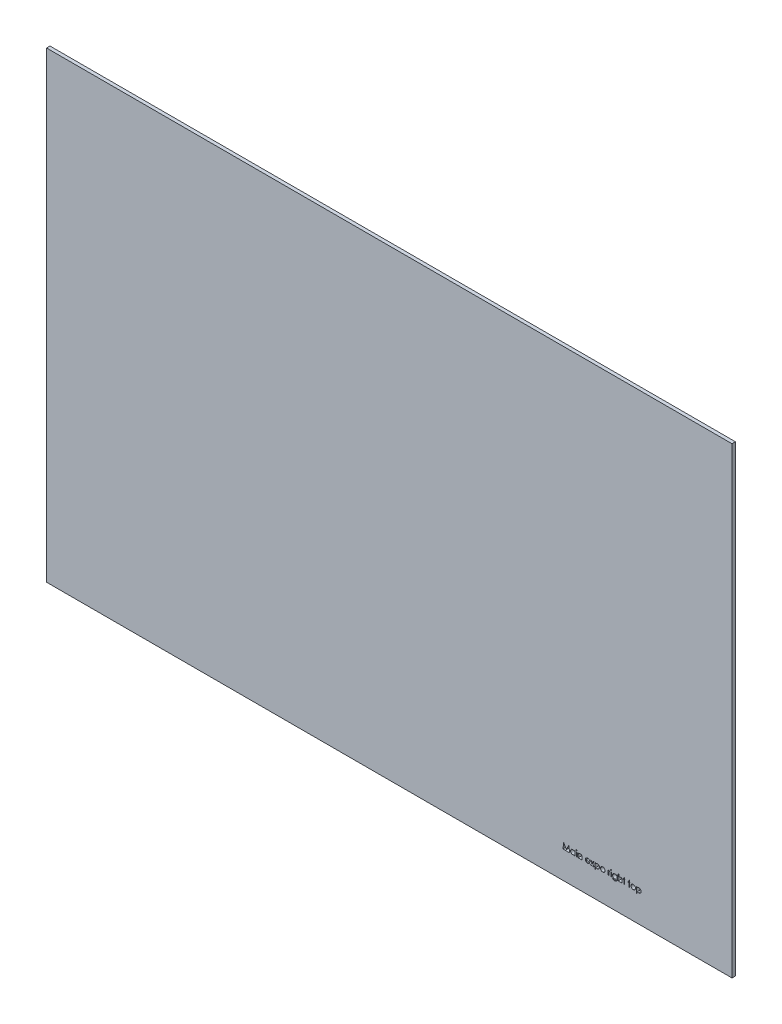
SolidWorks part; units mm, degrees
ref_plane "Front Plane" through (0, 0, 0) normal (0, 0, 1) x (1, 0, 0)
ref_plane "Top Plane" through (0, 0, 0) normal (0, 1, 0) x (1, 0, 0)
ref_plane "Right Plane" through (0, 0, 0) normal (1, 0, 0) x (0, 0, -1)
sketch "Sketch1" plane through (0, 0, 0) normal (0, 0, 1) x (1, 0, 0)
  line L0 (301.0601, -254.1343) -> (381.9081, -254.1343) construction
  line L1 (0, 0) -> (400, 0)
  line L2 (0, 0) -> (0, -270)
  line L3 (0, -270) -> (400, -270)
  line L4 (400, 0) -> (400, -270)
  line L5 (301.3293, -254.1343) -> (301.7913, -250.6343)
  line L6 (301.7913, -250.6343) -> (301.8362, -250.6343)
  line L7 (301.8362, -250.6343) -> (303.2812, -253.5061)
  line L8 (303.2812, -253.5061) -> (304.7227, -250.6343)
  line L9 (304.7227, -250.6343) -> (304.7683, -250.6343)
  line L10 (304.7683, -250.6343) -> (305.2331, -254.1343)
  line L11 (305.2331, -254.1343) -> (304.9176, -254.1343)
  line L12 (304.9176, -254.1343) -> (304.5825, -251.6158)
  line L13 (304.5825, -251.6158) -> (303.3191, -254.1343)
  line L14 (303.3191, -254.1343) -> (303.2483, -254.1343)
  line L15 (303.2483, -254.1343) -> (301.9799, -251.6102)
  line L16 (301.9799, -251.6102) -> (301.6455, -254.1343)
  line L17 (301.6455, -254.1343) -> (301.3293, -254.1343)
  line L18 (308.4639, -251.5766) -> (308.4639, -254.1343)
  line L19 (308.4639, -254.1343) -> (308.1498, -254.1343)
  line L20 (308.1498, -254.1343) -> (308.1498, -253.6919)
  line L21 (308.1498, -252.0498) -> (308.1498, -251.5766)
  line L22 (308.1498, -251.5766) -> (308.4639, -251.5766)
  line L23 (309.137, -251.5766) -> (309.4511, -251.5766)
  line L24 (309.4511, -251.5766) -> (309.4511, -254.1343)
  line L25 (309.4511, -254.1343) -> (309.137, -254.1343)
  line L26 (309.137, -254.1343) -> (309.137, -251.5766)
  line L27 (310.2139, -251.5766) -> (310.528, -251.5766)
  line L28 (310.528, -251.5766) -> (310.528, -252.0379)
  line L29 (312.4575, -252.8281) -> (312.4575, -254.1343)
  line L30 (312.4575, -254.1343) -> (312.1434, -254.1343)
  line L31 (312.1434, -254.1343) -> (312.1434, -252.9312)
  line L32 (310.528, -253.2095) -> (310.528, -254.1343)
  line L33 (310.528, -254.1343) -> (310.2139, -254.1343)
  line L34 (310.2139, -254.1343) -> (310.2139, -251.5766)
  line L35 (316.6208, -253.3266) -> (316.8998, -253.4731)
  line L36 (317.0344, -252.9227) -> (314.746, -252.9227)
  line L37 (314.7789, -252.6086) -> (316.7203, -252.6086)
  line L38 (317.4383, -251.5766) -> (317.812, -251.5766)
  line L39 (317.812, -251.5766) -> (318.4703, -252.4993)
  line L40 (318.4703, -252.4993) -> (319.1287, -251.5766)
  line L41 (319.1287, -251.5766) -> (319.5024, -251.5766)
  line L42 (319.5024, -251.5766) -> (318.6575, -252.7608)
  line L43 (318.6575, -252.7608) -> (319.637, -254.1343)
  line L44 (319.637, -254.1343) -> (319.2633, -254.1343)
  line L45 (319.2633, -254.1343) -> (318.4703, -253.023)
  line L46 (318.4703, -253.023) -> (317.6774, -254.1343)
  line L47 (317.6774, -254.1343) -> (317.3037, -254.1343)
  line L48 (317.3037, -254.1343) -> (318.2838, -252.7608)
  line L49 (318.2838, -252.7608) -> (317.4383, -251.5766)
  line L50 (319.996, -251.5766) -> (320.3101, -251.5766)
  line L51 (320.3101, -251.5766) -> (320.3101, -252.0498)
  line L52 (320.3101, -253.6708) -> (320.3101, -255.0766)
  line L53 (320.3101, -255.0766) -> (319.996, -255.0766)
  line L54 (319.996, -255.0766) -> (319.996, -251.5766)
  line L55 (327.7588, -251.5766) -> (328.0729, -251.5766)
  line L56 (328.0729, -251.5766) -> (328.0729, -251.9531)
  line L57 (328.9703, -251.6194) -> (328.7979, -251.8914)
  line L58 (328.0729, -253.2747) -> (328.0729, -254.1343)
  line L59 (328.0729, -254.1343) -> (327.7588, -254.1343)
  line L60 (327.7588, -254.1343) -> (327.7588, -251.5766)
  line L61 (329.2396, -251.5766) -> (329.5537, -251.5766)
  line L62 (329.5537, -251.5766) -> (329.5537, -254.1343)
  line L63 (329.5537, -254.1343) -> (329.2396, -254.1343)
  line L64 (329.2396, -254.1343) -> (329.2396, -251.5766)
  line L65 (332.5601, -251.5766) -> (332.8742, -251.5766)
  line L66 (332.8742, -251.5766) -> (332.8742, -253.6063)
  line L67 (330.2716, -254.3138) -> (330.5857, -254.3138)
  line L68 (332.5601, -253.7767) -> (332.5601, -253.6442)
  line L69 (332.5601, -252.0239) -> (332.5601, -251.5766)
  line L70 (333.5921, -250.5445) -> (333.9062, -250.5445)
  line L71 (333.9062, -250.5445) -> (333.9062, -252.0597)
  line L72 (335.8357, -252.8281) -> (335.8357, -254.1343)
  line L73 (335.8357, -254.1343) -> (335.5216, -254.1343)
  line L74 (335.5216, -254.1343) -> (335.5216, -252.9312)
  line L75 (333.9062, -253.2095) -> (333.9062, -254.1343)
  line L76 (333.9062, -254.1343) -> (333.5921, -254.1343)
  line L77 (333.5921, -254.1343) -> (333.5921, -250.5445)
  line L78 (336.8678, -250.5445) -> (337.1819, -250.5445)
  line L79 (337.1819, -250.5445) -> (337.1819, -251.5766)
  line L80 (337.1819, -251.5766) -> (337.6306, -251.5766)
  line L81 (337.6306, -251.5766) -> (337.6306, -251.8907)
  line L82 (337.6306, -251.8907) -> (337.1819, -251.8907)
  line L83 (337.1819, -251.8907) -> (337.1819, -254.1343)
  line L84 (337.1819, -254.1343) -> (336.8678, -254.1343)
  line L85 (336.8678, -254.1343) -> (336.8678, -251.8907)
  line L86 (336.8678, -251.8907) -> (336.419, -251.8907)
  line L87 (336.419, -251.8907) -> (336.419, -251.5766)
  line L88 (336.419, -251.5766) -> (336.8678, -251.5766)
  line L89 (336.8678, -251.5766) -> (336.8678, -250.5445)
  line L90 (339.8293, -250.5445) -> (340.1434, -250.5445)
  line L91 (340.1434, -250.5445) -> (340.1434, -251.5766)
  line L92 (340.1434, -251.5766) -> (340.5921, -251.5766)
  line L93 (340.5921, -251.5766) -> (340.5921, -251.8907)
  line L94 (340.5921, -251.8907) -> (340.1434, -251.8907)
  line L95 (340.1434, -251.8907) -> (340.1434, -254.1343)
  line L96 (340.1434, -254.1343) -> (339.8293, -254.1343)
  line L97 (339.8293, -254.1343) -> (339.8293, -251.8907)
  line L98 (339.8293, -251.8907) -> (339.3806, -251.8907)
  line L99 (339.3806, -251.8907) -> (339.3806, -251.5766)
  line L100 (339.3806, -251.5766) -> (339.8293, -251.5766)
  line L101 (339.8293, -251.5766) -> (339.8293, -250.5445)
  line L102 (344.3165, -251.5766) -> (344.6306, -251.5766)
  line L103 (344.6306, -251.5766) -> (344.6306, -252.0498)
  line L104 (344.6306, -253.6708) -> (344.6306, -255.0766)
  line L105 (344.6306, -255.0766) -> (344.3165, -255.0766)
  line L106 (344.3165, -255.0766) -> (344.3165, -251.5766)
  spline S0 degree 3 poles (308.1498, -253.6919) (308.0826, -253.7713) (307.9741, -253.8818) (307.8074, -253.9965) (307.6788, -254.0647) (307.5438, -254.1158) (307.3538, -254.1652) (307.2054, -254.18) (307.1051, -254.1791) knots 0 0 0 0 0.262085 0.38627 0.507165 0.6273 0.748145 1 1 1 1
  spline S1 degree 3 poles (307.1051, -254.1791) (307.0161, -254.1789) (306.8838, -254.1674) (306.7138, -254.1266) (306.5925, -254.0847) (306.4768, -254.0291) (306.3658, -253.9626) (306.2599, -253.8833) (306.1608, -253.7928) (306.0696, -253.6944) (305.9895, -253.5894) (305.9228, -253.4784) (305.867, -253.3626) (305.824, -253.2413) (305.7833, -253.0706) (305.7718, -252.9379) (305.7716, -252.8484) knots 0 0 0 0 0.127433 0.189004 0.24993 0.310668 0.372329 0.434939 0.499576 0.564191 0.626735 0.688109 0.749294 0.810331 0.871901 1 1 1 1
  spline S2 degree 3 poles (305.7716, -252.8484) (305.7721, -252.7606) (305.7829, -252.63) (305.8249, -252.4623) (305.8684, -252.3429) (305.9242, -252.2286) (305.9921, -252.1192) (306.0722, -252.0144) (306.1644, -251.9167) (306.2643, -251.8265) (306.3713, -251.7481) (306.4825, -251.6804) (306.5997, -251.6267) (306.7213, -251.5833) (306.8925, -251.5427) (307.0255, -251.5325) (307.115, -251.5317) knots 0 0 0 0 0.126079 0.186904 0.247574 0.308003 0.369132 0.432033 0.496791 0.561611 0.624914 0.686726 0.748079 0.809582 0.871631 1 1 1 1
  spline S3 degree 3 poles (307.115, -251.5317) (307.2172, -251.532) (307.3689, -251.5451) (307.5609, -251.5991) (307.6956, -251.653) (307.8227, -251.7247) (307.9846, -251.8478) (308.0879, -251.9649) (308.1498, -252.0498) knots 0 0 0 0 0.254654 0.376015 0.495255 0.614798 0.738106 1 1 1 1
  spline S4 degree 3 poles (307.1192, -251.8458) (307.0287, -251.8462) (306.8933, -251.8612) (306.7223, -251.9178) (306.6013, -251.975) (306.4887, -252.047) (306.388, -252.1342) (306.2984, -252.234) (306.2231, -252.3461) (306.1618, -252.4663) (306.1039, -252.6334) (306.0846, -252.7644) (306.0857, -252.8519) knots 0 0 0 0 0.169593 0.252476 0.336244 0.419505 0.502036 0.584775 0.669846 0.754185 0.836658 1 1 1 1
  spline S5 degree 3 poles (306.0857, -252.8519) (306.0865, -252.9388) (306.1031, -253.0704) (306.163, -253.2372) (306.2242, -253.3584) (306.3009, -253.471) (306.3897, -253.5727) (306.4917, -253.6602) (306.6046, -253.7335) (306.7252, -253.7926) (306.8947, -253.8479) (307.0275, -253.8655) (307.1164, -253.865) knots 0 0 0 0 0.162859 0.245484 0.330807 0.416493 0.499893 0.583048 0.667158 0.751312 0.833785 1 1 1 1
  spline S6 degree 3 poles (307.1164, -253.865) (307.2067, -253.8647) (307.3423, -253.849) (307.5151, -253.793) (307.6389, -253.7351) (307.7542, -253.6634) (307.8577, -253.5794) (307.9452, -253.4817) (308.0195, -253.3743) (308.0776, -253.2566) (308.1351, -253.0872) (308.1493, -252.9517) (308.1498, -252.861) knots 0 0 0 0 0.168664 0.252552 0.33824 0.423103 0.505556 0.586176 0.667136 0.748499 0.830452 1 1 1 1
  spline S7 degree 3 poles (308.1498, -252.861) (308.1496, -252.7915) (308.1408, -252.6885) (308.1096, -252.5563) (308.0772, -252.4628) (308.0347, -252.3742) (307.9835, -252.2897) (307.9226, -252.2099) (307.853, -252.1357) (307.7768, -252.0681) (307.6962, -252.0078) (307.6103, -251.9582) (307.5204, -251.9171) (307.4263, -251.8845) (307.2927, -251.8548) (307.1893, -251.8448) (307.1192, -251.8458) knots 0 0 0 0 0.129188 0.191219 0.251913 0.312507 0.373494 0.435152 0.498741 0.562095 0.624187 0.685476 0.746097 0.807612 0.869967 1 1 1 1
  spline S8 degree 3 poles (309.2926, -250.4997) (309.3306, -250.4997) (309.388, -250.5084) (309.4558, -250.5432) (309.5003, -250.5777) (309.5385, -250.6182) (309.5745, -250.6813) (309.5859, -250.7346) (309.5857, -250.7703) knots 0 0 0 0 0.258284 0.384341 0.51198 0.638632 0.75923 1 1 1 1
  spline S9 degree 3 poles (309.5857, -250.7703) (309.5858, -250.8052) (309.5745, -250.8577) (309.5383, -250.9196) (309.5004, -250.9601) (309.4557, -250.9946) (309.388, -251.0294) (309.3306, -251.038) (309.2926, -251.0381) knots 0 0 0 0 0.237546 0.357497 0.484917 0.613329 0.74015 1 1 1 1
  spline S10 degree 3 poles (309.2926, -251.0381) (309.2552, -251.0384) (309.1987, -251.0289) (309.1317, -250.9945) (309.087, -250.9604) (309.0498, -250.9194) (309.0135, -250.8578) (309.0023, -250.8052) (309.0024, -250.7703) knots 0 0 0 0 0.256661 0.384213 0.513365 0.640443 0.761085 1 1 1 1
  spline S11 degree 3 poles (309.0024, -250.7703) (309.0022, -250.7347) (309.0135, -250.6813) (309.0496, -250.6185) (309.087, -250.5774) (309.1317, -250.5432) (309.1987, -250.5088) (309.2552, -250.4994) (309.2926, -250.4997) knots 0 0 0 0 0.242149 0.363437 0.489745 0.618115 0.744894 1 1 1 1
  spline S12 degree 3 poles (310.528, -252.0379) (310.5914, -251.9557) (310.6923, -251.8408) (310.8496, -251.7202) (310.9696, -251.6501) (311.0952, -251.5973) (311.2707, -251.5457) (311.4087, -251.5322) (311.5012, -251.5317) knots 0 0 0 0 0.273569 0.398988 0.51993 0.63811 0.756589 1 1 1 1
  spline S13 degree 3 poles (311.5012, -251.5317) (311.5936, -251.5323) (311.7314, -251.5473) (311.902, -251.6101) (312.0186, -251.6732) (312.1237, -251.7519) (312.2161, -251.8434) (312.2924, -251.9488) (312.3436, -252.0465) (312.3774, -252.1332) (312.3986, -252.2074) (312.4166, -252.2901) (312.4323, -252.3811) (312.4428, -252.4809) (312.4544, -252.6306) (312.4583, -252.7474) (312.4575, -252.8281) knots 0 0 0 0 0.151178 0.223488 0.295543 0.366976 0.437131 0.507044 0.57856 0.616614 0.658756 0.704491 0.754803 0.809332 0.868274 1 1 1 1
  spline S14 degree 3 poles (312.1434, -252.9312) (312.1429, -252.8645) (312.1428, -252.7692) (312.1389, -252.6479) (312.1349, -252.5705) (312.1291, -252.5022) (312.1218, -252.4292) (312.1133, -252.3793) (312.1062, -252.3492) knots 0 0 0 0 0.34211 0.489826 0.623254 0.74008 0.841483 1 1 1 1
  spline S15 degree 3 poles (312.1062, -252.3492) (312.0887, -252.2724) (312.049, -252.1628) (311.9608, -252.0412) (311.8829, -251.969) (311.7917, -251.9129) (311.6473, -251.8587) (311.5281, -251.8453) (311.4465, -251.8458) knots 0 0 0 0 0.260833 0.378476 0.493178 0.609281 0.729981 1 1 1 1
  spline S16 degree 3 poles (311.4465, -251.8458) (311.3965, -251.8456) (311.3218, -251.8513) (311.2251, -251.8722) (311.1547, -251.893) (311.0872, -251.9217) (311.0205, -251.9542) (310.9569, -251.9948) (310.8953, -252.0399) (310.838, -252.09) (310.7847, -252.1429) (310.7372, -252.1991) (310.6941, -252.2579) (310.6569, -252.3201) (310.6134, -252.4068) (310.589, -252.4758) (310.5764, -252.5231) knots 0 0 0 0 0.126627 0.188984 0.25023 0.312351 0.374574 0.438148 0.50292 0.567974 0.630771 0.692935 0.754398 0.815218 0.876117 1 1 1 1
  spline S17 degree 3 poles (310.5764, -252.5231) (310.567, -252.5605) (310.5566, -252.622) (310.5462, -252.7109) (310.5392, -252.7918) (310.5349, -252.8825) (310.5283, -253.0227) (310.5285, -253.1329) (310.528, -253.2095) knots 0 0 0 0 0.167615 0.271052 0.38946 0.520843 0.666399 1 1 1 1
  spline S18 degree 3 poles (316.8998, -253.4731) (316.8583, -253.5508) (316.7888, -253.6598) (316.6819, -253.7896) (316.5968, -253.8713) (316.5071, -253.9426) (316.4124, -254.0049) (316.3121, -254.058) (316.2063, -254.1028) (316.094, -254.1372) (315.9316, -254.1705) (315.8047, -254.1791) (315.7184, -254.1791) knots 0 0 0 0 0.181661 0.265874 0.346355 0.4246 0.501903 0.579992 0.658443 0.738672 0.821894 1 1 1 1
  spline S19 degree 3 poles (315.7184, -254.1791) (315.6227, -254.1791) (315.4817, -254.1681) (315.3025, -254.125) (315.1793, -254.081) (315.0645, -254.0236) (314.958, -253.9536) (314.8592, -253.8715) (314.7712, -253.7765) (314.692, -253.6748) (314.622, -253.5689) (314.5636, -253.4589) (314.516, -253.3456) (314.4776, -253.2298) (314.4416, -253.0693) (314.4328, -252.9455) (314.4319, -252.8624) knots 0 0 0 0 0.139629 0.204797 0.268135 0.329814 0.391301 0.453434 0.516552 0.579631 0.641119 0.701294 0.76081 0.819932 0.87892 1 1 1 1
  spline S20 degree 3 poles (314.4319, -252.8624) (314.4328, -252.7846) (314.4401, -252.6685) (314.4717, -252.518) (314.5039, -252.4091) (314.5454, -252.3035) (314.6136, -252.166) (314.6788, -252.07) (314.7263, -252.0085) knots 0 0 0 0 0.253768 0.377428 0.500551 0.623296 0.746578 1 1 1 1
  spline S21 degree 3 poles (314.7263, -252.0085) (314.7869, -251.9327) (314.8857, -251.8269) (315.0403, -251.7161) (315.1619, -251.6481) (315.2923, -251.5964) (315.4788, -251.5439) (315.6267, -251.5329) (315.7261, -251.5317) knots 0 0 0 0 0.253589 0.374643 0.49534 0.616325 0.739759 1 1 1 1
  spline S22 degree 3 poles (315.7261, -251.5317) (315.829, -251.5313) (315.9809, -251.5462) (316.1735, -251.5994) (316.3073, -251.6545) (316.433, -251.7257) (316.5913, -251.8448) (316.6947, -251.9545) (316.7561, -252.0351) knots 0 0 0 0 0.259033 0.38188 0.502258 0.622752 0.744743 1 1 1 1
  spline S23 degree 3 poles (316.7561, -252.0351) (316.802, -252.094) (316.8619, -252.1896) (316.9255, -252.3264) (316.9639, -252.4353) (316.9949, -252.5491) (317.0255, -252.7115) (317.0328, -252.8375) (317.0344, -252.9227) knots 0 0 0 0 0.236255 0.356174 0.47725 0.60154 0.729618 1 1 1 1
  spline S24 degree 3 poles (314.746, -252.9227) (314.7478, -252.989) (314.7566, -253.0868) (314.7869, -253.2121) (314.8182, -253.2991) (314.856, -253.3821) (314.9024, -253.4602) (314.9578, -253.5333) (315.0195, -253.6018) (315.0882, -253.6629) (315.1605, -253.7175) (315.2374, -253.7633) (315.3183, -253.8005) (315.403, -253.8296) (315.523, -253.8567) (315.6162, -253.8654) (315.6792, -253.865) knots 0 0 0 0 0.134476 0.198391 0.260753 0.321829 0.383037 0.444653 0.507398 0.569825 0.630778 0.690929 0.750945 0.811049 0.872331 1 1 1 1
  spline S25 degree 3 poles (315.6792, -253.865) (315.7414, -253.8653) (315.8347, -253.858) (315.9565, -253.8325) (316.0458, -253.8066) (316.1313, -253.7751) (316.2106, -253.737) (316.2835, -253.6948) (316.3516, -253.6466) (316.4176, -253.5876) (316.5111, -253.4828) (316.5782, -253.3931) (316.6208, -253.3266) knots 0 0 0 0 0.163879 0.245659 0.327726 0.40861 0.485749 0.559169 0.630268 0.705306 0.792065 1 1 1 1
  spline S26 degree 3 poles (316.7203, -252.6086) (316.7005, -252.5279) (316.6608, -252.414) (316.5884, -252.2771) (316.5268, -252.1915) (316.457, -252.1155) (316.3763, -252.0491) (316.2859, -251.9896) (316.1861, -251.9395) (316.0805, -251.8968) (315.9327, -251.8583) (315.8187, -251.8447) (315.7423, -251.8458) knots 0 0 0 0 0.185231 0.267501 0.3444 0.419595 0.496891 0.576638 0.660268 0.745387 0.83004 1 1 1 1
  spline S27 degree 3 poles (315.7423, -251.8458) (315.6803, -251.8457) (315.5883, -251.8524) (315.47, -251.8781) (315.3853, -251.904) (315.3046, -251.9386) (315.1996, -251.9931) (315.1287, -252.0473) (315.0832, -252.0856) knots 0 0 0 0 0.259141 0.384162 0.505992 0.629098 0.750669 1 1 1 1
  spline S28 degree 3 poles (315.0832, -252.0856) (315.0483, -252.115) (315.0011, -252.1659) (314.9444, -252.2406) (314.905, -252.3037) (314.869, -252.3723) (314.8228, -252.4729) (314.7954, -252.5533) (314.7789, -252.6086) knots 0 0 0 0 0.22258 0.3385 0.458709 0.585535 0.717518 1 1 1 1
  spline S29 degree 3 poles (320.3101, -252.0498) (320.3722, -251.9645) (320.4767, -251.8486) (320.6379, -251.7244) (320.7651, -251.653) (320.8995, -251.5992) (321.0907, -251.5451) (321.2418, -251.532) (321.3435, -251.5317) knots 0 0 0 0 0.263045 0.386061 0.505771 0.625178 0.746148 1 1 1 1
  spline S30 degree 3 poles (321.3435, -251.5317) (321.4332, -251.5326) (321.5664, -251.5426) (321.7379, -251.5833) (321.8594, -251.6267) (321.9767, -251.6804) (322.0879, -251.7481) (322.1948, -251.8265) (322.2948, -251.9167) (322.3871, -252.0144) (322.4669, -252.1194) (322.5358, -252.2283) (322.5915, -252.3429) (322.635, -252.4622) (322.677, -252.63) (322.6878, -252.7606) (322.6883, -252.8484) knots 0 0 0 0 0.128636 0.190653 0.252125 0.313446 0.375227 0.438498 0.503285 0.56801 0.630879 0.692154 0.752552 0.813191 0.873985 1 1 1 1
  spline S31 degree 3 poles (322.6883, -252.8484) (322.6881, -252.9379) (322.6766, -253.0706) (322.6359, -253.2413) (322.5929, -253.3626) (322.5372, -253.4786) (322.4695, -253.5892) (322.3896, -253.6944) (322.2983, -253.7927) (322.1993, -253.8833) (322.0934, -253.9626) (321.9824, -254.0291) (321.8667, -254.0847) (321.7454, -254.1266) (321.5751, -254.1675) (321.4426, -254.1788) (321.3533, -254.1791) knots 0 0 0 0 0.128034 0.189574 0.25058 0.311733 0.37325 0.435763 0.500346 0.564949 0.627528 0.689157 0.749865 0.81076 0.8723 1 1 1 1
  spline S32 degree 3 poles (321.3533, -254.1791) (321.2529, -254.1803) (321.1044, -254.1631) (320.914, -254.1106) (320.7798, -254.054) (320.6517, -253.9817) (320.4866, -253.8622) (320.3776, -253.751) (320.3101, -253.6708) knots 0 0 0 0 0.250548 0.37123 0.492116 0.613401 0.737997 1 1 1 1
  spline S33 degree 3 poles (321.3407, -251.8458) (321.2706, -251.8448) (321.1672, -251.8549) (321.0335, -251.8845) (320.9394, -251.9173) (320.8492, -251.9577) (320.7635, -252.0082) (320.6824, -252.0679) (320.6062, -252.1356) (320.5373, -252.2101) (320.4764, -252.2897) (320.4252, -252.3742) (320.3826, -252.4628) (320.3503, -252.5563) (320.3191, -252.6885) (320.3103, -252.7915) (320.3101, -252.861) knots 0 0 0 0 0.130024 0.192374 0.253884 0.314896 0.375806 0.438242 0.501591 0.564881 0.626533 0.687516 0.748106 0.808796 0.870822 1 1 1 1
  spline S34 degree 3 poles (320.3101, -252.861) (320.3102, -252.9518) (320.3254, -253.0869) (320.3814, -253.2567) (320.4399, -253.3742) (320.5138, -253.4822) (320.6029, -253.5789) (320.7064, -253.6637) (320.8224, -253.7351) (320.9469, -253.793) (321.12, -253.8487) (321.2555, -253.8649) (321.3456, -253.865) knots 0 0 0 0 0.169344 0.251061 0.332326 0.413189 0.494299 0.576654 0.661785 0.747765 0.831967 1 1 1 1
  spline S35 degree 3 poles (321.3456, -253.865) (321.4341, -253.8656) (321.5663, -253.8477) (321.7352, -253.7928) (321.8554, -253.7333) (321.9682, -253.6603) (322.0701, -253.5727) (322.1591, -253.4712) (322.235, -253.3582) (322.296, -253.237) (322.3573, -253.0706) (322.3732, -252.9387) (322.3742, -252.8519) knots 0 0 0 0 0.165574 0.248159 0.332033 0.416257 0.499525 0.583039 0.668596 0.754035 0.83692 1 1 1 1
  spline S36 degree 3 poles (322.3742, -252.8519) (322.3754, -252.7644) (322.3558, -252.6335) (322.2983, -252.4661) (322.2358, -252.3465) (322.1616, -252.2338) (322.0719, -252.1342) (321.9712, -252.047) (321.8586, -251.975) (321.7376, -251.9178) (321.5666, -251.8612) (321.4312, -251.8462) (321.3407, -251.8458) knots 0 0 0 0 0.163349 0.245826 0.330367 0.415198 0.497941 0.580476 0.66374 0.747513 0.830399 1 1 1 1
  spline S37 degree 3 poles (324.5519, -251.5317) (324.6459, -251.5307) (324.7852, -251.5443) (324.9633, -251.5889) (325.0891, -251.6342) (325.2075, -251.6949) (325.3598, -251.7924) (325.4615, -251.8851) (325.5236, -251.9531) knots 0 0 0 0 0.258332 0.382134 0.503804 0.624693 0.746871 1 1 1 1
  spline S38 degree 3 poles (325.5236, -251.9531) (325.5806, -252.0154) (325.657, -252.1154) (325.7393, -252.2597) (325.7884, -252.3719) (325.827, -252.4883) (325.8642, -252.6513) (325.8737, -252.7775) (325.8742, -252.8624) knots 0 0 0 0 0.253834 0.376506 0.498534 0.621368 0.744565 1 1 1 1
  spline S39 degree 3 poles (325.8742, -252.8624) (325.8747, -252.948) (325.863, -253.0751) (325.8243, -253.2395) (325.7836, -253.3574) (325.7312, -253.4713) (325.6673, -253.5807) (325.5914, -253.6858) (325.5054, -253.7858) (325.4104, -253.878) (325.3073, -253.9583) (325.1981, -254.0271) (325.0815, -254.0826) (324.9584, -254.1263) (324.7823, -254.1681) (324.6448, -254.1788) (324.5519, -254.1791) knots 0 0 0 0 0.123337 0.183265 0.243172 0.302898 0.363774 0.425605 0.489659 0.553785 0.616222 0.677854 0.739517 0.802097 0.865866 1 1 1 1
  spline S40 degree 3 poles (324.5519, -254.1791) (324.4585, -254.1787) (324.3204, -254.1682) (324.1439, -254.1263) (324.0207, -254.0824) (323.9035, -254.0271) (323.7938, -253.9585) (323.6906, -253.878) (323.5955, -253.7858) (323.5095, -253.6858) (323.4336, -253.5807) (323.3697, -253.4713) (323.3174, -253.3574) (323.2766, -253.2395) (323.2379, -253.0751) (323.2262, -252.948) (323.2267, -252.8624) knots 0 0 0 0 0.134635 0.198324 0.260825 0.322714 0.384555 0.446913 0.510958 0.574931 0.636685 0.697483 0.757134 0.816966 0.876818 1 1 1 1
  spline S41 degree 3 poles (323.2267, -252.8624) (323.2272, -252.7777) (323.2368, -252.6517) (323.2738, -252.4892) (323.3125, -252.3733) (323.362, -252.2616) (323.4432, -252.1168) (323.5209, -252.0177) (323.5773, -251.9552) knots 0 0 0 0 0.255238 0.378679 0.501088 0.622714 0.746241 1 1 1 1
  spline S42 degree 3 poles (323.5773, -251.9552) (323.6389, -251.8863) (323.7414, -251.7945) (323.8934, -251.695) (324.0131, -251.6355) (324.1388, -251.5887) (324.3177, -251.5443) (324.4573, -251.5308) (324.5519, -251.5317) knots 0 0 0 0 0.252713 0.374819 0.496436 0.617911 0.741288 1 1 1 1
  spline S43 degree 3 poles (324.5505, -251.8458) (324.4835, -251.846) (324.3839, -251.855) (324.256, -251.8861) (324.1645, -251.9187) (324.0769, -251.9608) (323.993, -252.0125) (323.9125, -252.0732) (323.8372, -252.1426) (323.768, -252.2185) (323.7075, -252.2993) (323.6561, -252.3839) (323.6132, -252.4721) (323.5814, -252.565) (323.5499, -252.6952) (323.541, -252.7964) (323.5408, -252.8645) knots 0 0 0 0 0.126044 0.187165 0.247399 0.30838 0.36978 0.432584 0.497641 0.562401 0.625557 0.687332 0.748313 0.809791 0.871768 1 1 1 1
  spline S44 degree 3 poles (323.5408, -252.8645) (323.5411, -252.9532) (323.5567, -253.0865) (323.615, -253.2545) (323.6735, -253.3741) (323.747, -253.4848) (323.8334, -253.5835) (323.9321, -253.6687) (324.0417, -253.7394) (324.16, -253.7954) (324.3284, -253.8493) (324.4612, -253.8661) (324.5505, -253.865) knots 0 0 0 0 0.168179 0.251488 0.335841 0.419834 0.502345 0.583649 0.665931 0.748717 0.831047 1 1 1 1
  spline S45 degree 3 poles (324.5505, -253.865) (324.6397, -253.8659) (324.7723, -253.8496) (324.9403, -253.7953) (325.0586, -253.7394) (325.1681, -253.6684) (325.2675, -253.584) (325.3532, -253.4845) (325.4266, -253.374) (325.4861, -253.2547) (325.5441, -253.0865) (325.5599, -252.9533) (325.5601, -252.8645) knots 0 0 0 0 0.168983 0.250908 0.333708 0.416005 0.49766 0.579893 0.663902 0.748466 0.831791 1 1 1 1
  spline S46 degree 3 poles (325.5601, -252.8645) (325.5599, -252.7964) (325.551, -252.6952) (325.5196, -252.565) (325.4876, -252.4721) (325.445, -252.3836) (325.3926, -252.2996) (325.3323, -252.2182) (325.2623, -252.1429) (325.187, -252.0731) (325.1065, -252.0125) (325.0228, -251.961) (324.9354, -251.9184) (324.8439, -251.8864) (324.7164, -251.8548) (324.6172, -251.8462) (324.5505, -251.8458) knots 0 0 0 0 0.128274 0.19027 0.251768 0.312769 0.374793 0.43797 0.503047 0.568125 0.63095 0.692369 0.752973 0.813641 0.874355 1 1 1 1
  spline S47 degree 3 poles (328.0729, -251.9531) (328.1159, -251.8854) (328.1839, -251.7916) (328.2897, -251.6889) (328.3673, -251.6304) (328.4477, -251.5866) (328.5553, -251.5439) (328.6408, -251.5321) (328.6969, -251.5317) knots 0 0 0 0 0.306112 0.438367 0.560541 0.675317 0.786114 1 1 1 1
  spline S48 degree 3 poles (328.6969, -251.5317) (328.7419, -251.5321) (328.8383, -251.549) (328.926, -251.5925) (328.9703, -251.6194) knots 0 0 0 0 0.463523 1 1 1 1
  spline S49 degree 3 poles (328.7979, -251.8914) (328.7692, -251.8787) (328.7178, -251.8555) (328.662, -251.8461) (328.6373, -251.8458) knots 0 0 0 0 0.56023 1 1 1 1
  spline S50 degree 3 poles (328.6373, -251.8458) (328.5858, -251.8457) (328.5069, -251.8646) (328.4119, -251.9215) (328.3538, -251.9696) (328.3087, -252.0162) (328.2766, -252.0569) (328.2471, -252.1024) (328.2189, -252.1522) (328.1933, -252.2069) (328.1604, -252.2879) (328.1409, -252.3524) (328.129, -252.3969) knots 0 0 0 0 0.191338 0.295191 0.410312 0.47193 0.536425 0.603119 0.674118 0.749332 0.828283 1 1 1 1
  spline S51 degree 3 poles (328.129, -252.3969) (328.1172, -252.4416) (328.1058, -252.5167) (328.0935, -252.6265) (328.0864, -252.7294) (328.0798, -252.846) (328.0746, -253.0293) (328.0723, -253.1737) (328.0729, -253.2747) knots 0 0 0 0 0.156938 0.2586 0.375891 0.508166 0.656238 1 1 1 1
  spline S52 degree 3 poles (329.3952, -250.4997) (329.4332, -250.4997) (329.4906, -250.5084) (329.5583, -250.5432) (329.6029, -250.5777) (329.6411, -250.6182) (329.6771, -250.6813) (329.6885, -250.7346) (329.6883, -250.7703) knots 0 0 0 0 0.258284 0.384341 0.51198 0.638632 0.75923 1 1 1 1
  spline S53 degree 3 poles (329.6883, -250.7703) (329.6884, -250.8052) (329.677, -250.8577) (329.6409, -250.9196) (329.6029, -250.9601) (329.5583, -250.9946) (329.4906, -251.0294) (329.4332, -251.038) (329.3952, -251.0381) knots 0 0 0 0 0.237546 0.357497 0.484917 0.613329 0.74015 1 1 1 1
  spline S54 degree 3 poles (329.3952, -251.0381) (329.3578, -251.0384) (329.3013, -251.0289) (329.2342, -250.9945) (329.1896, -250.9604) (329.1524, -250.9194) (329.1161, -250.8578) (329.1049, -250.8052) (329.1049, -250.7703) knots 0 0 0 0 0.256661 0.384213 0.513365 0.640443 0.761085 1 1 1 1
  spline S55 degree 3 poles (329.1049, -250.7703) (329.1048, -250.7347) (329.116, -250.6813) (329.1522, -250.6185) (329.1896, -250.5774) (329.2342, -250.5432) (329.3013, -250.5088) (329.3578, -250.4994) (329.3952, -250.4997) knots 0 0 0 0 0.242149 0.363437 0.489745 0.618115 0.744894 1 1 1 1
  spline S56 degree 3 poles (332.8742, -253.6063) (332.8737, -253.6898) (332.8727, -253.8106) (332.8614, -253.9652) (332.8522, -254.0679) (332.8389, -254.1615) (332.8185, -254.2692) (332.7981, -254.3446) (332.7809, -254.3909) knots 0 0 0 0 0.315489 0.456291 0.585864 0.705429 0.813371 1 1 1 1
  spline S57 degree 3 poles (332.7809, -254.3909) (332.7602, -254.448) (332.7226, -254.5302) (332.6601, -254.632) (332.6074, -254.7024) (332.5482, -254.7674) (332.4841, -254.8283) (332.4139, -254.8839) (332.3375, -254.9332) (332.2566, -254.9776) (332.1715, -255.016) (332.0825, -255.0495) (331.9888, -255.0746) (331.8919, -255.0963) (331.7547, -255.1156) (331.6493, -255.122) (331.5778, -255.1215) knots 0 0 0 0 0.120906 0.179424 0.237607 0.295938 0.354218 0.413537 0.474087 0.535121 0.596988 0.66002 0.724277 0.790012 0.857748 1 1 1 1
  spline S58 degree 3 poles (331.5778, -255.1215) (331.4744, -255.1228) (331.323, -255.1097) (331.128, -255.0718) (330.9944, -255.0302) (330.8711, -254.9791) (330.759, -254.9205) (330.659, -254.8534) (330.5689, -254.7769) (330.4876, -254.6859) (330.38, -254.5355) (330.3133, -254.4061) (330.2716, -254.3138) knots 0 0 0 0 0.188474 0.27684 0.362137 0.443437 0.520166 0.59271 0.662917 0.735419 0.814881 1 1 1 1
  spline S59 degree 3 poles (330.5857, -254.3138) (330.6318, -254.3941) (330.7164, -254.5031) (330.854, -254.6205) (330.9674, -254.6905) (331.0936, -254.7431) (331.2863, -254.7954) (331.4414, -254.8069) (331.5477, -254.8074) knots 0 0 0 0 0.243805 0.360062 0.475112 0.593525 0.71935 1 1 1 1
  spline S60 degree 3 poles (331.5477, -254.8074) (331.653, -254.8068) (331.8068, -254.7953) (331.9984, -254.7431) (332.123, -254.6905) (332.232, -254.6261) (332.3261, -254.5541) (332.4022, -254.4729) (332.4534, -254.3981) (332.4852, -254.3315) (332.5055, -254.2742) (332.522, -254.2093) (332.5358, -254.1372) (332.5471, -254.0576) (332.5572, -253.9368) (332.5606, -253.8422) (332.5601, -253.7767) knots 0 0 0 0 0.189264 0.274463 0.355023 0.43092 0.501086 0.566608 0.629721 0.662711 0.698766 0.738611 0.782581 0.830409 0.882578 1 1 1 1
  spline S61 degree 3 poles (332.5601, -253.6442) (332.4991, -253.7211) (332.3965, -253.8273) (332.2366, -253.9408) (332.1076, -254.0104) (331.9717, -254.066) (331.7828, -254.1186) (331.6361, -254.135) (331.5378, -254.1343) knots 0 0 0 0 0.250895 0.374719 0.499826 0.624964 0.749039 1 1 1 1
  spline S62 degree 3 poles (331.5378, -254.1343) (331.4797, -254.1345) (331.393, -254.1283) (331.279, -254.1108) (331.1954, -254.0917) (331.1132, -254.0672) (331.0324, -254.0366) (330.9525, -254.002) (330.8748, -253.9612) (330.8002, -253.9158) (330.7293, -253.8667) (330.6623, -253.814) (330.6, -253.7573) (330.5423, -253.6967) (330.4887, -253.6327) (330.4398, -253.5646) (330.3948, -253.4934) (330.3557, -253.4189) (330.3214, -253.3425) (330.2916, -253.2645) (330.2679, -253.1845) (330.2497, -253.1027) (330.2315, -252.9905) (330.2273, -252.9046) (330.2267, -252.847) knots 0 0 0 0 0.085222 0.127202 0.169025 0.210882 0.252963 0.295628 0.338553 0.381463 0.423582 0.465066 0.506312 0.54704 0.587676 0.628675 0.669946 0.711036 0.751996 0.792673 0.833446 0.874191 0.915494 1 1 1 1
  spline S63 degree 3 poles (330.2267, -252.847) (330.2265, -252.7891) (330.2328, -252.7029) (330.25, -252.5895) (330.2702, -252.5068) (330.2945, -252.4252) (330.3247, -252.3452) (330.3609, -252.267) (330.4019, -252.1903) (330.448, -252.1162) (330.4985, -252.0459) (330.5536, -251.9798) (330.6123, -251.9173) (330.6756, -251.859) (330.7433, -251.8049) (330.8148, -251.7543) (330.8902, -251.7082) (330.9685, -251.6674) (331.0476, -251.6302) (331.1286, -251.6007) (331.21, -251.5747) (331.2932, -251.5562) (331.4053, -251.5371) (331.4907, -251.5318) (331.5477, -251.5317) knots 0 0 0 0 0.083905 0.125069 0.166158 0.20721 0.248491 0.289878 0.33217 0.374476 0.416225 0.45761 0.499073 0.540553 0.582249 0.62455 0.667433 0.710323 0.752467 0.794065 0.835216 0.876228 0.917446 1 1 1 1
  spline S64 degree 3 poles (331.5477, -251.5317) (331.6405, -251.5319) (331.7787, -251.545) (331.9563, -251.5903) (332.0842, -251.6383) (332.2091, -251.7039) (332.3776, -251.8235) (332.4885, -251.9402) (332.5601, -252.0239) knots 0 0 0 0 0.238762 0.354755 0.470359 0.589144 0.716329 1 1 1 1
  spline S65 degree 3 poles (331.5729, -251.8458) (331.4819, -251.8455) (331.3465, -251.8625) (331.1741, -251.9183) (331.0525, -251.9773) (330.9385, -252.0494) (330.8375, -252.1368) (330.7491, -252.2365) (330.6743, -252.3478) (330.6148, -252.4678) (330.5581, -252.637) (330.5402, -252.7702) (330.5408, -252.8596) knots 0 0 0 0 0.169309 0.252218 0.336756 0.420595 0.502741 0.584804 0.668268 0.751823 0.833629 1 1 1 1
  spline S66 degree 3 poles (330.5408, -252.8596) (330.5406, -252.9263) (330.5487, -253.0252) (330.5789, -253.1515) (330.6103, -253.2402) (330.6493, -253.3246) (330.6983, -253.4044) (330.7559, -253.4795) (330.8218, -253.5494) (330.8944, -253.6131) (330.9731, -253.669) (331.0578, -253.7147) (331.1465, -253.7543) (331.2414, -253.7831) (331.3766, -253.8132) (331.4825, -253.8198) (331.554, -253.8202) knots 0 0 0 0 0.127803 0.189056 0.248395 0.307691 0.366977 0.42734 0.488795 0.550674 0.612045 0.673369 0.73493 0.79781 0.862892 1 1 1 1
  spline S67 degree 3 poles (331.554, -253.8202) (331.6262, -253.8202) (331.7326, -253.8127) (331.8688, -253.7842) (331.9632, -253.7546) (332.0523, -253.7169) (332.1352, -253.6692) (332.2136, -253.6148) (332.2849, -253.5514) (332.3494, -253.4815) (332.4057, -253.4055) (332.4536, -253.3244) (332.4933, -253.2383) (332.5235, -253.1466) (332.5514, -253.0143) (332.5609, -252.9115) (332.5601, -252.8414) knots 0 0 0 0 0.137122 0.201487 0.263765 0.32456 0.384739 0.444905 0.505232 0.565494 0.6251 0.68435 0.743883 0.804608 0.867239 1 1 1 1
  spline S68 degree 3 poles (332.5601, -252.8414) (332.5605, -252.7504) (332.5459, -252.6155) (332.4916, -252.4462) (332.4358, -252.3298) (332.3658, -252.2229) (332.2815, -252.1276) (332.1843, -252.0437) (332.0746, -251.9738) (331.9566, -251.9174) (331.7913, -251.8605) (331.66, -251.847) (331.5729, -251.8458) knots 0 0 0 0 0.174349 0.257613 0.339527 0.420997 0.501579 0.582542 0.666133 0.750049 0.832743 1 1 1 1
  spline S69 degree 3 poles (333.9062, -252.0597) (333.9694, -251.9757) (334.0741, -251.8624) (334.2296, -251.7356) (334.3499, -251.6617) (334.475, -251.6034) (334.6498, -251.5476) (334.7874, -251.5319) (334.8794, -251.5317) knots 0 0 0 0 0.273996 0.400684 0.522555 0.641534 0.759969 1 1 1 1
  spline S70 degree 3 poles (334.8794, -251.5317) (334.9718, -251.5323) (335.1096, -251.5473) (335.2802, -251.6101) (335.3969, -251.6732) (335.5017, -251.7519) (335.5945, -251.8427) (335.6704, -251.948) (335.722, -252.0452) (335.7555, -252.1318) (335.7768, -252.206) (335.7948, -252.2887) (335.8105, -252.3799) (335.821, -252.48) (335.8327, -252.6301) (335.8365, -252.7472) (335.8357, -252.8281) knots 0 0 0 0 0.151155 0.223454 0.295497 0.36692 0.436794 0.506696 0.577864 0.615912 0.658048 0.703776 0.75408 0.808979 0.867913 1 1 1 1
  spline S71 degree 3 poles (335.5216, -252.9312) (335.5212, -252.8645) (335.5209, -252.7692) (335.5172, -252.6479) (335.5128, -252.5705) (335.5082, -252.5022) (335.5006, -252.4292) (335.4923, -252.3793) (335.4852, -252.3492) knots 0 0 0 0 0.342141 0.489871 0.623312 0.740056 0.841468 1 1 1 1
  spline S72 degree 3 poles (335.4852, -252.3492) (335.4658, -252.2726) (335.4252, -252.1631) (335.3369, -252.0412) (335.2591, -251.9692) (335.1686, -251.9129) (335.0246, -251.8585) (334.9056, -251.8454) (334.824, -251.8458) knots 0 0 0 0 0.261954 0.379638 0.494379 0.609866 0.729887 1 1 1 1
  spline S73 degree 3 poles (334.824, -251.8458) (334.774, -251.8456) (334.6993, -251.8513) (334.6026, -251.8722) (334.5322, -251.893) (334.4649, -251.9215) (334.3985, -251.9544) (334.3351, -251.9947) (334.2735, -252.0399) (334.2162, -252.09) (334.1629, -252.1429) (334.1154, -252.1991) (334.0723, -252.2579) (334.0351, -252.3201) (333.9916, -252.4068) (333.9672, -252.4758) (333.9546, -252.5231) knots 0 0 0 0 0.126694 0.189084 0.250363 0.312516 0.374243 0.43785 0.502657 0.567745 0.630576 0.692772 0.754268 0.815121 0.876051 1 1 1 1
  spline S74 degree 3 poles (333.9546, -252.5231) (333.9452, -252.56) (333.9347, -252.621) (333.9244, -252.7095) (333.9174, -252.7904) (333.9131, -252.8814) (333.9065, -253.022) (333.9067, -253.1326) (333.9062, -253.2095) knots 0 0 0 0 0.165611 0.269045 0.387448 0.518827 0.665394 1 1 1 1
  spline S75 degree 3 poles (342.366, -251.5317) (342.4601, -251.5307) (342.5993, -251.5443) (342.7774, -251.5889) (342.9032, -251.6342) (343.0216, -251.6949) (343.1739, -251.7924) (343.2756, -251.8851) (343.3377, -251.9531) knots 0 0 0 0 0.258332 0.382134 0.503804 0.624693 0.746871 1 1 1 1
  spline S76 degree 3 poles (343.3377, -251.9531) (343.3947, -252.0154) (343.4711, -252.1154) (343.5534, -252.2597) (343.6025, -252.3719) (343.6411, -252.4883) (343.6783, -252.6513) (343.6878, -252.7775) (343.6883, -252.8624) knots 0 0 0 0 0.253834 0.376506 0.498534 0.621368 0.744565 1 1 1 1
  spline S77 degree 3 poles (343.6883, -252.8624) (343.6888, -252.948) (343.6771, -253.0751) (343.6384, -253.2395) (343.5977, -253.3574) (343.5453, -253.4713) (343.4814, -253.5807) (343.4055, -253.6858) (343.3195, -253.7858) (343.2245, -253.878) (343.1214, -253.9583) (343.0122, -254.0271) (342.8956, -254.0826) (342.7725, -254.1263) (342.5964, -254.1681) (342.4589, -254.1788) (342.366, -254.1791) knots 0 0 0 0 0.123337 0.183265 0.243172 0.302898 0.363774 0.425605 0.489659 0.553785 0.616222 0.677854 0.739517 0.802097 0.865866 1 1 1 1
  spline S78 degree 3 poles (342.366, -254.1791) (342.2726, -254.1787) (342.1345, -254.1682) (341.958, -254.1263) (341.8348, -254.0824) (341.7176, -254.0271) (341.6079, -253.9585) (341.5047, -253.878) (341.4096, -253.7858) (341.3236, -253.6858) (341.2477, -253.5807) (341.1838, -253.4713) (341.1315, -253.3574) (341.0907, -253.2395) (341.052, -253.0751) (341.0403, -252.948) (341.0408, -252.8624) knots 0 0 0 0 0.134635 0.198324 0.260825 0.322714 0.384555 0.446913 0.510958 0.574931 0.636685 0.697483 0.757134 0.816966 0.876818 1 1 1 1
  spline S79 degree 3 poles (341.0408, -252.8624) (341.0413, -252.7777) (341.0509, -252.6517) (341.0879, -252.4892) (341.1266, -252.3733) (341.1761, -252.2616) (341.2573, -252.1168) (341.335, -252.0177) (341.3914, -251.9552) knots 0 0 0 0 0.255238 0.378679 0.501088 0.622714 0.746241 1 1 1 1
  spline S80 degree 3 poles (341.3914, -251.9552) (341.453, -251.8863) (341.5555, -251.7945) (341.7075, -251.695) (341.8272, -251.6355) (341.9529, -251.5887) (342.1318, -251.5443) (342.2714, -251.5308) (342.366, -251.5317) knots 0 0 0 0 0.252713 0.374819 0.496436 0.617911 0.741288 1 1 1 1
  spline S81 degree 3 poles (342.3646, -251.8458) (342.2976, -251.846) (342.198, -251.855) (342.0701, -251.8861) (341.9786, -251.9187) (341.891, -251.9608) (341.8071, -252.0125) (341.7266, -252.0732) (341.6513, -252.1426) (341.5821, -252.2185) (341.5216, -252.2993) (341.4702, -252.3839) (341.4273, -252.4721) (341.3955, -252.565) (341.364, -252.6952) (341.3551, -252.7964) (341.3549, -252.8645) knots 0 0 0 0 0.126044 0.187165 0.247399 0.30838 0.36978 0.432584 0.497641 0.562401 0.625557 0.687332 0.748313 0.809791 0.871768 1 1 1 1
  spline S82 degree 3 poles (341.3549, -252.8645) (341.3552, -252.9532) (341.3708, -253.0865) (341.4291, -253.2545) (341.4876, -253.3741) (341.5611, -253.4848) (341.6475, -253.5835) (341.7462, -253.6687) (341.8558, -253.7394) (341.9742, -253.7954) (342.1426, -253.8493) (342.2753, -253.8661) (342.3646, -253.865) knots 0 0 0 0 0.168179 0.251488 0.335841 0.419834 0.502345 0.583649 0.665931 0.748717 0.831047 1 1 1 1
  spline S83 degree 3 poles (342.3646, -253.865) (342.4538, -253.8659) (342.5864, -253.8496) (342.7544, -253.7953) (342.8727, -253.7394) (342.9822, -253.6684) (343.0816, -253.584) (343.1673, -253.4845) (343.2407, -253.374) (343.3002, -253.2547) (343.3582, -253.0865) (343.374, -252.9533) (343.3742, -252.8645) knots 0 0 0 0 0.168983 0.250908 0.333708 0.416005 0.49766 0.579893 0.663902 0.748466 0.831791 1 1 1 1
  spline S84 degree 3 poles (343.3742, -252.8645) (343.374, -252.7964) (343.3651, -252.6952) (343.3337, -252.565) (343.3017, -252.4721) (343.2591, -252.3836) (343.2067, -252.2996) (343.1464, -252.2182) (343.0764, -252.1429) (343.0011, -252.0731) (342.9206, -252.0125) (342.8369, -251.961) (342.7495, -251.9184) (342.658, -251.8864) (342.5305, -251.8548) (342.4313, -251.8462) (342.3646, -251.8458) knots 0 0 0 0 0.128274 0.19027 0.251768 0.312769 0.374793 0.43797 0.503047 0.568125 0.63095 0.692369 0.752973 0.813641 0.874355 1 1 1 1
  spline S85 degree 3 poles (344.6306, -252.0498) (344.6927, -251.9645) (344.7972, -251.8486) (344.9585, -251.7244) (345.0856, -251.653) (345.22, -251.5992) (345.4112, -251.5451) (345.5623, -251.532) (345.664, -251.5317) knots 0 0 0 0 0.263045 0.386061 0.505771 0.625178 0.746148 1 1 1 1
  spline S86 degree 3 poles (345.664, -251.5317) (345.7537, -251.5326) (345.887, -251.5426) (346.0584, -251.5833) (346.18, -251.6267) (346.2972, -251.6804) (346.4084, -251.7481) (346.5154, -251.8265) (346.6153, -251.9167) (346.7076, -252.0144) (346.7874, -252.1194) (346.8563, -252.2283) (346.912, -252.3429) (346.9556, -252.4622) (346.9975, -252.63) (347.0083, -252.7606) (347.0088, -252.8484) knots 0 0 0 0 0.128636 0.190653 0.252125 0.313446 0.375227 0.438498 0.503285 0.56801 0.630879 0.692154 0.752552 0.813191 0.873985 1 1 1 1
  spline S87 degree 3 poles (347.0088, -252.8484) (347.0086, -252.9379) (346.9971, -253.0706) (346.9564, -253.2413) (346.9134, -253.3626) (346.8577, -253.4786) (346.79, -253.5892) (346.7102, -253.6944) (346.6189, -253.7927) (346.5198, -253.8833) (346.4139, -253.9626) (346.3029, -254.0291) (346.1872, -254.0847) (346.0659, -254.1266) (345.8956, -254.1675) (345.7631, -254.1788) (345.6739, -254.1791) knots 0 0 0 0 0.128034 0.189574 0.25058 0.311733 0.37325 0.435763 0.500346 0.564949 0.627528 0.689157 0.749865 0.81076 0.8723 1 1 1 1
  spline S88 degree 3 poles (345.6739, -254.1791) (345.5734, -254.1803) (345.4249, -254.1631) (345.2346, -254.1106) (345.1004, -254.054) (344.9722, -253.9817) (344.8072, -253.8622) (344.6981, -253.751) (344.6306, -253.6708) knots 0 0 0 0 0.250548 0.37123 0.492116 0.613401 0.737997 1 1 1 1
  spline S89 degree 3 poles (345.6612, -251.8458) (345.5911, -251.8448) (345.4877, -251.8549) (345.354, -251.8845) (345.2599, -251.9173) (345.1697, -251.9577) (345.084, -252.0082) (345.0029, -252.0679) (344.9267, -252.1356) (344.8578, -252.2101) (344.7969, -252.2897) (344.7457, -252.3742) (344.7032, -252.4628) (344.6708, -252.5563) (344.6396, -252.6885) (344.6308, -252.7915) (344.6306, -252.861) knots 0 0 0 0 0.130024 0.192374 0.253884 0.314896 0.375806 0.438242 0.501591 0.564881 0.626533 0.687516 0.748106 0.808796 0.870822 1 1 1 1
  spline S90 degree 3 poles (344.6306, -252.861) (344.6308, -252.9518) (344.6459, -253.0869) (344.7019, -253.2567) (344.7604, -253.3742) (344.8343, -253.4822) (344.9234, -253.5789) (345.0269, -253.6637) (345.1429, -253.7351) (345.2674, -253.793) (345.4405, -253.8487) (345.576, -253.8649) (345.6661, -253.865) knots 0 0 0 0 0.169344 0.251061 0.332326 0.413189 0.494299 0.576654 0.661785 0.747765 0.831967 1 1 1 1
  spline S91 degree 3 poles (345.6661, -253.865) (345.7546, -253.8656) (345.8868, -253.8477) (346.0557, -253.7928) (346.1759, -253.7333) (346.2887, -253.6603) (346.3906, -253.5727) (346.4796, -253.4712) (346.5555, -253.3582) (346.6166, -253.237) (346.6778, -253.0706) (346.6937, -252.9387) (346.6947, -252.8519) knots 0 0 0 0 0.165574 0.248159 0.332033 0.416257 0.499525 0.583039 0.668596 0.754035 0.83692 1 1 1 1
  spline S92 degree 3 poles (346.6947, -252.8519) (346.6959, -252.7644) (346.6763, -252.6335) (346.6188, -252.4661) (346.5563, -252.3465) (346.4821, -252.2338) (346.3924, -252.1342) (346.2918, -252.047) (346.1791, -251.975) (346.0581, -251.9178) (345.8871, -251.8612) (345.7517, -251.8462) (345.6612, -251.8458) knots 0 0 0 0 0.163349 0.245826 0.330367 0.415198 0.497941 0.580476 0.66374 0.747513 0.830399 1 1 1 1
  dimension "D1" = 400
  dimension "D2" = 270
extrude "Boss-Extrude1" add sketch "Sketch1" along normal blind 2
